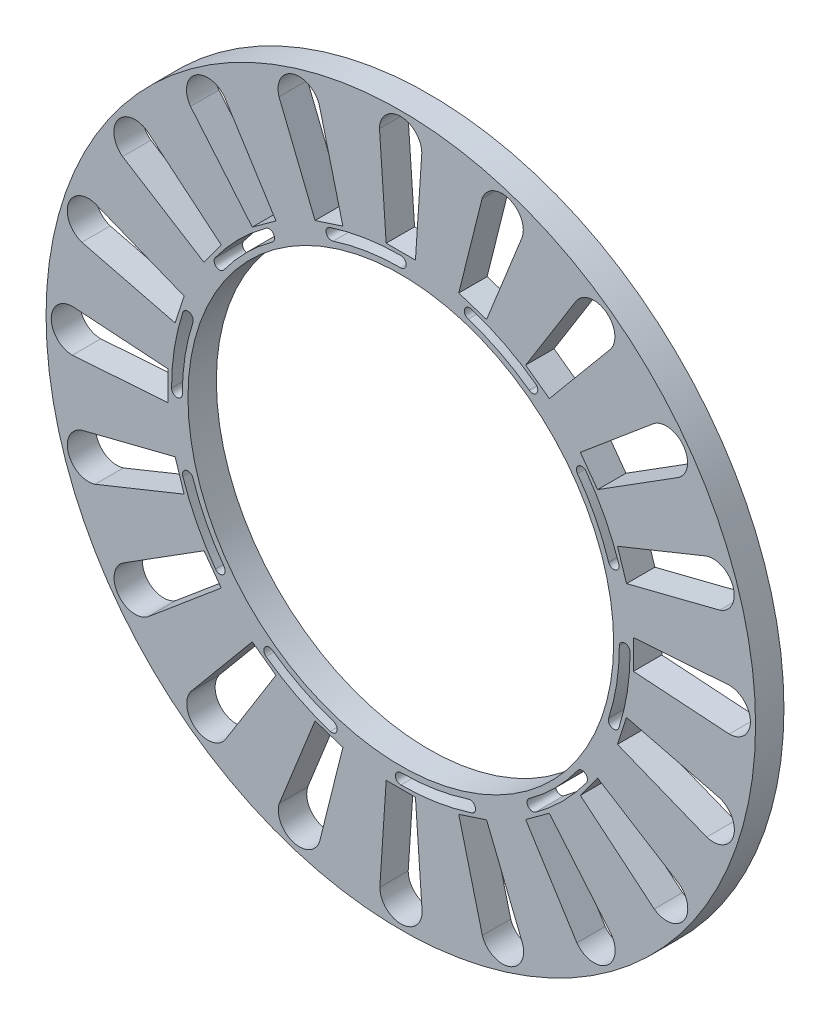
SolidWorks part; units mm, degrees
ref_plane "Front Plane" through (0, 0, 0) normal (0, 0, 1) x (1, 0, 0)
ref_plane "Top Plane" through (0, 0, 0) normal (0, 1, 0) x (1, 0, 0)
ref_plane "Right Plane" through (0, 0, 0) normal (1, 0, 0) x (0, 0, -1)
sketch "Sketch1" plane through (0, 0, 0) normal (0, 0, 1) x (1, 0, 0)
  circle A0 centre (0, 0) radius 25
  circle A1 centre (0, 0) radius 10
  dimension "D1" = 50
  dimension "D2" = 20
extrude "Boss-Extrude1" add sketch "Sketch1" along normal blind 2 contours A0
sketch "Sketch2" plane through (0, 0, 0) normal (0, 0, -1) x (-1, 0, 0)
  circle A0 centre (0, 0) radius 15
  dimension "D1" = 30
extrude "Cut-Extrude1" cut sketch "Sketch2" against normal blind 5
sketch "Sketch8" plane through (0, 0, 2) normal (0, 0, 1) x (1, 0, 0)
  line L0 (0, 25) -> (0, -25) construction
  line L1 (-1.5029, 23.1436) -> (-1.0313, 16.3882)
  line L2 (1.4787, 23.1436) -> (1.0313, 16.3882)
  line L3 (-1.0313, 16.3882) -> (1.0313, 16.3882)
  circle A0 centre (0, 0) radius 25 construction
  arc A1 (-1.5029, 23.1436) -> (1.4787, 23.1436) centre (-0.0121, 23.1436) cw
  point P14 (0, 16.3882)
  dimension "D1" = 1.4908
  dimension "D2" = 6.7553
extrude "Cut-Extrude4" cut sketch "Sketch8" against normal blind 10
pattern_circular "CirPattern3" count 20 over 360 about axis through (0, 0, 0) along (0, 0, 1) of "Cut-Extrude4"
sketch "Sketch9" plane through (0, 0, 2) normal (0, 0, 1) x (1, 0, 0)
  arc A0 (-4.8915, 15) -> (0, 15.7774) centre (0, 0) cw construction
  arc A1 (0, 16.1557) -> (-5.0087, 15.3597) centre (0, 0) ccw
  arc A2 (0, 15.3991) -> (-4.7742, 14.6403) centre (0, 0) ccw
  arc A3 (0, 15.3991) -> (0, 16.1557) centre (0, 15.7774) ccw
  arc A4 (-5.0087, 15.3597) -> (-4.7742, 14.6403) centre (-4.8915, 15) ccw
  point P4 (-2.4764, 15.5818)
  dimension "D1" = 15.3991
  dimension "D2" = 0.3783
extrude "Cut-Extrude5" cut sketch "Sketch9" against normal blind 10
pattern_circular "CirPattern4" count 10 over 360 about axis through (0, 0, 0) along (0, 0, 1) of "Cut-Extrude5"
